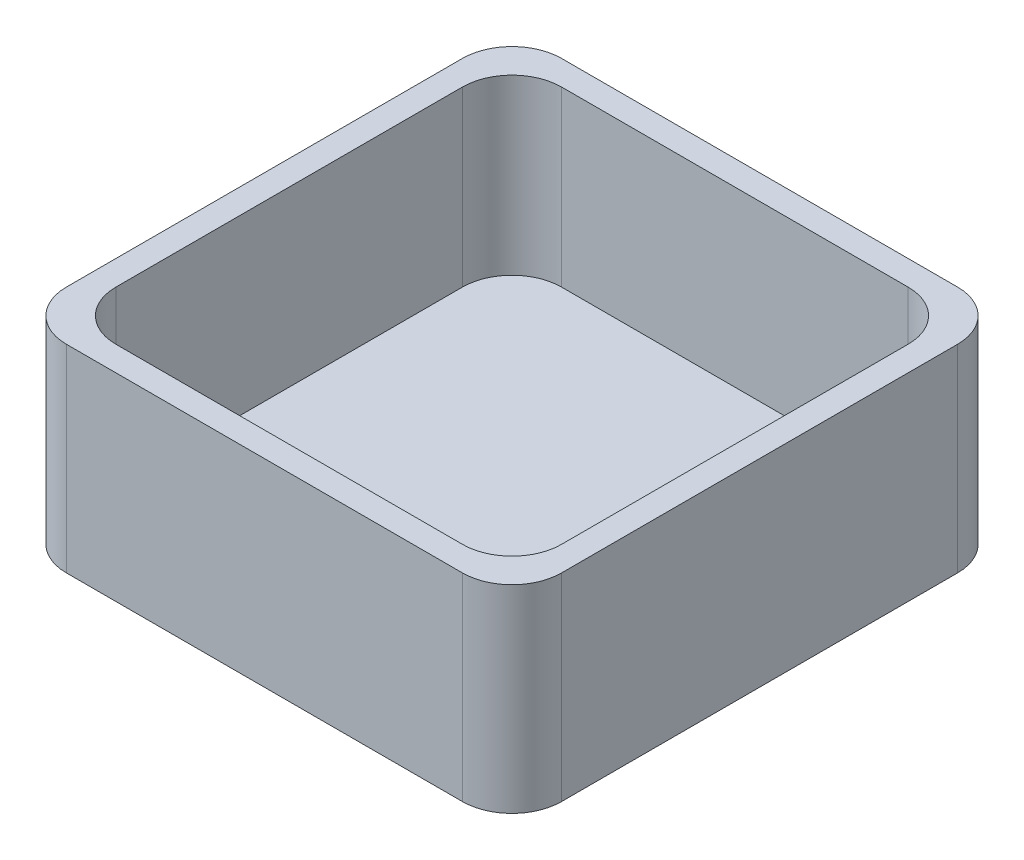
SolidWorks part; units mm, degrees
ref_plane "Front Plane" through (0, 0, 0) normal (0, 0, 1) x (1, 0, 0)
ref_plane "Top Plane" through (0, 0, 0) normal (0, 1, 0) x (1, 0, 0)
ref_plane "Right Plane" through (0, 0, 0) normal (1, 0, 0) x (0, 0, -1)
sketch "Sketch1" plane through (0, 0, 0) normal (0, 1, 0) x (1, 0, 0)
  line L1 (0, 0) -> (100, 0)
  line L2 (0, 0) -> (0, -100)
  line L3 (0, -100) -> (100, -100)
  line L4 (100, 0) -> (100, -100)
  dimension "D1" = 100
  dimension "D2" = 100
extrude "Boss-Extrude1" add sketch "Sketch1" along normal blind 40
sketch "Sketch2" plane through (0, 40, 0) normal (0, 1, 0) x (1, 0, 0)
  line L0 (100, 0) -> (0, 0) construction
  line L1 (5, -5) -> (95, -5)
  line L2 (5, -5) -> (5, -95)
  line L3 (5, -95) -> (95, -95)
  line L4 (95, -5) -> (95, -95)
  line L5 (100, -100) -> (100, 0) construction
  line L6 (0, 0) -> (0, -100) construction
  line L7 (0, -100) -> (100, -100) construction
  dimension "D1" = 5
  dimension "D2" = 5
  dimension "D3" = 5
  dimension "D4" = 5
extrude "Cut-Extrude1" cut sketch "Sketch2" against normal blind 35
fillet "Fillet1" radius 10 8 edges at (95, 22.5, 5) (100, 20, 0) (100, 20, 100) (95, 22.5, 95) (5, 22.5, 95) (0, 20, 100) (5, 22.5, 5) (0, 20, 0)
